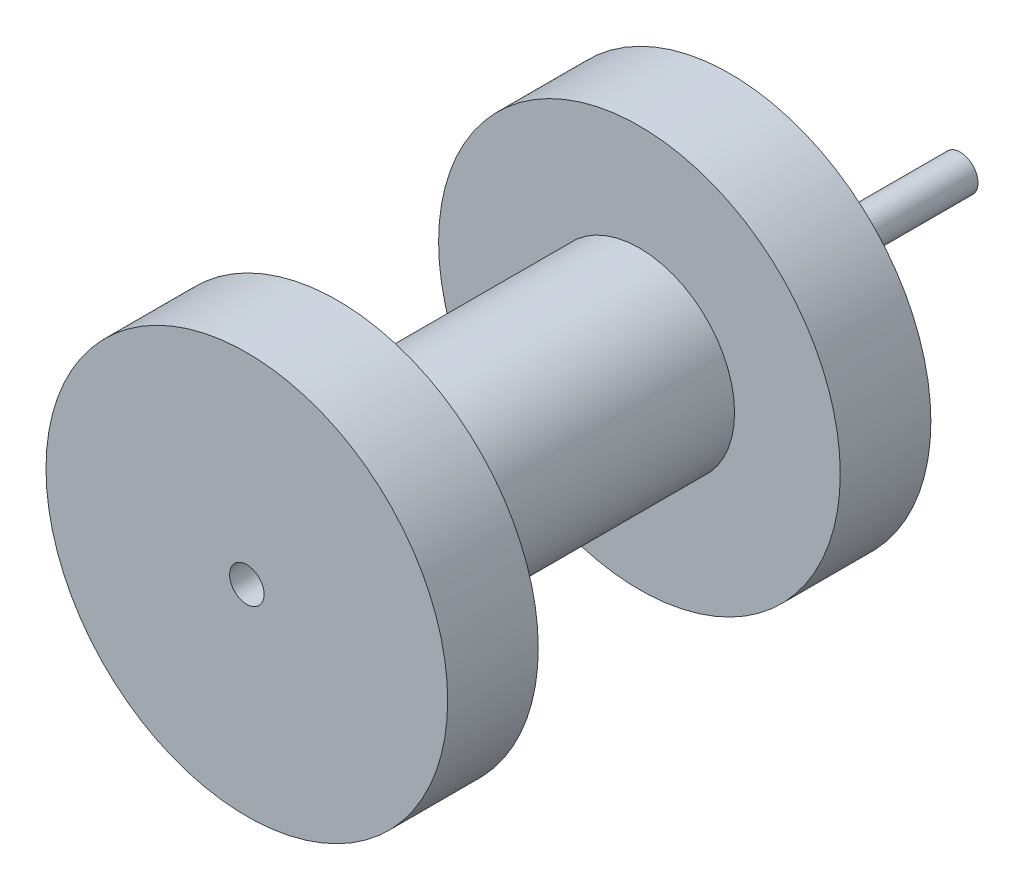
SolidWorks part; units mm, degrees
ref_plane "Front Plane" through (0, 0, 0) normal (0, 0, 1) x (1, 0, 0)
ref_plane "Top Plane" through (0, 0, 0) normal (0, 1, 0) x (1, 0, 0)
ref_plane "Right Plane" through (0, 0, 0) normal (1, 0, 0) x (0, 0, -1)
sketch "Sketch1" plane through (0, 0, 0) normal (0, 0, 1) x (1, 0, 0)
  circle A0 centre (0, 0) radius 1.5001
extrude "Boss-Extrude1" add sketch "Sketch1" along normal mid plane 59.9948
shell "Shell3" thickness 0.0508
ref_plane "Plane2" through (0, 0, -31.875) normal (0, 0, 1) x (1, 0, 0)
ref_plane "Plane3" through (0, 0, 29.9974) normal (0, 0, 1) x (1, 0, 0)
sketch "Sketch5" plane through (0, 0, 29.9974) normal (0, 0, 1) x (1, 0, 0)
  circle A0 centre (0, 0) radius 1.4493
  circle A1 centre (0, 0) radius 16.891
extrude "Boss-Extrude8" add sketch "Sketch5" against normal blind 7.62
ref_plane "Plane5" through (0, 0, 22.3774) normal (0, 0, -1) x (-1, 0, 0)
sketch "Sketch6" plane through (0, 0, 22.3774) normal (0, 0, -1) x (-1, 0, 0)
  circle A0 centre (0, 0) radius 7.62
  circle A1 centre (0, 0) radius 8
extrude "Boss-Extrude9" add sketch "Sketch6" along normal blind 25.4
ref_plane "Plane6" through (0, 0, -3.0226) normal (0, 0, -1) x (-1, 0, 0)
sketch "Sketch7" plane through (0, 0, -3.0226) normal (0, 0, -1) x (-1, 0, 0)
  circle A0 centre (0, 0) radius 1.5001
  circle A1 centre (0, 0) radius 16.891
extrude "Boss-Extrude10" add sketch "Sketch7" along normal blind 7.62
sketch "Sketch8" plane through (0, 0, 29.9974) normal (0, 0, 1) x (1, 0, 0)
  circle A0 centre (0, 0) radius 1.4493
  circle A1 centre (0, 0) radius 8
extrude "Boss-Extrude11" add sketch "Sketch8" against normal blind 2.54
